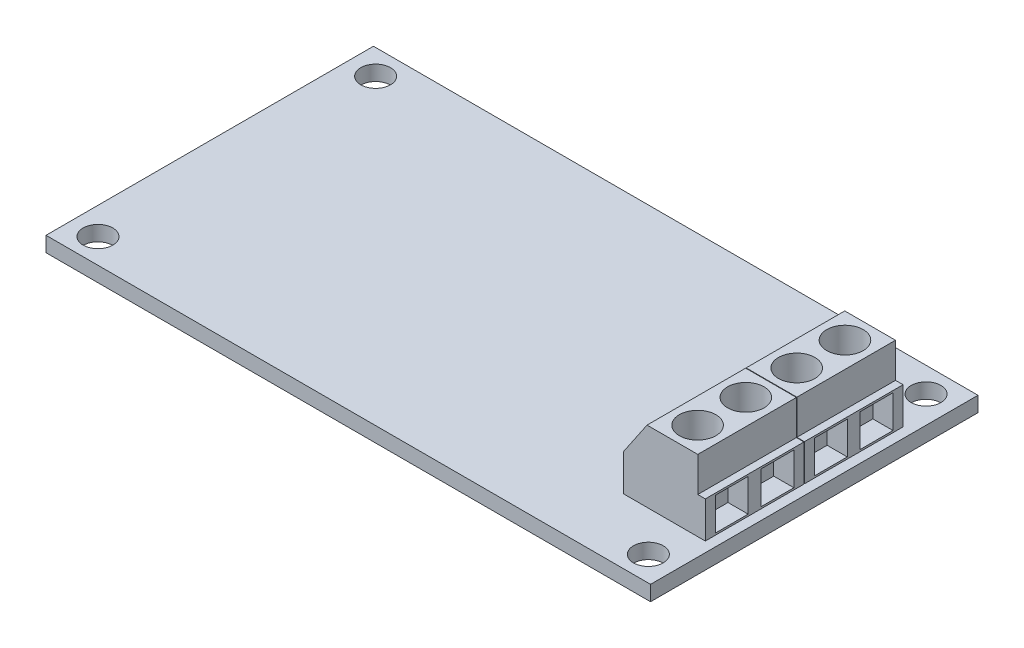
SolidWorks part; units mm, degrees
ref_plane "Plan de face" through (0, 0, 0) normal (0, 0, 1) x (1, 0, 0)
ref_plane "Plan de dessus" through (0, 0, 0) normal (0, 1, 0) x (1, 0, 0)
ref_plane "Plan de droite" through (0, 0, 0) normal (1, 0, 0) x (0, 0, -1)
sketch "Esquisse1" plane through (0, 0, 0) normal (0, 1, 0) x (1, 0, 0)
  line L1 (-30.48, 16.51) -> (30.48, 16.51)
  line L2 (-30.48, 16.51) -> (-30.48, -16.51)
  line L3 (-30.48, -16.51) -> (30.48, -16.51)
  line L4 (30.48, 16.51) -> (30.48, -16.51)
  line L5 (-30.48, 16.51) -> (30.48, -16.51) construction
  line L6 (-30.48, -16.51) -> (30.48, 16.51) construction
  point P0 (0, 0)
  dimension "D1" = 60.96
  dimension "D2" = 33.02
extrude "Boss.-Extru.1" add sketch "Esquisse1" along normal blind 1.524
sketch "Esquisse3" plane through (0, 1.524, 0) normal (0, 1, 0) x (1, 0, 0)
  line L0 (30.48, 0) -> (29.464, 0) construction
  line L1 (30.48, -16.51) -> (30.48, 16.51) construction
  line L2 (29.464, -9.9695) -> (29.464, 9.9695)
  line L3 (29.464, 9.9695) -> (21.209, 9.9695)
  line L4 (21.209, 9.9695) -> (21.209, -9.9695)
  line L5 (21.209, 0) -> (29.464, 0)
  line L6 (29.464, 0) -> (0, 0) construction
  line L7 (29.464, -9.9695) -> (21.209, -9.9695)
  dimension "D1" = 1.016
  dimension "D2" = 9.9695
  dimension "D3" = 8.255
extrude "Boss.-Extru.2" add sketch "Esquisse3" along normal blind 3.683 contours L7 L2 L5 L4 | L4 L5 L2 L3
sketch "Esquisse5" plane through (0, 5.207, 0) normal (0, 1, 0) x (1, 0, 0)
  line L0 (30.48, 0) -> (28.702, 0) construction
  line L1 (30.48, -16.51) -> (30.48, 16.51) construction
  line L2 (28.702, 0) -> (28.702, 9.9695)
  line L3 (29.464, 9.9695) -> (21.209, 9.9695) construction
  line L4 (28.702, 9.9695) -> (23.5862, 9.9695)
  line L5 (23.5862, 9.9695) -> (23.5862, -9.9695)
  line L6 (29.464, -9.9695) -> (21.209, -9.9695) construction
  line L7 (23.5862, -9.9695) -> (28.702, -9.9695)
  line L8 (28.702, -9.9695) -> (28.702, 0)
  dimension "D1" = 1.778
extrude "Boss.-Extru.3" add sketch "Esquisse5" along normal blind 3.5052
sketch "Esquisse6" plane through (0, 0, 9.9695) normal (0, 0, 1) x (1, 0, 0)
  line L0 (23.5862, 8.7122) -> (21.209, 5.207)
  line L1 (21.209, 5.207) -> (23.5862, 5.207)
  line L2 (23.5862, 5.207) -> (23.5862, 8.7122)
extrude "Boss.-Extru.4" add sketch "Esquisse6" against normal up to surface (19.939 mm away) up to face at (25.7403, 5.1626, -9.9695)
sketch "Esquisse7" plane through (0, 8.7122, 0) normal (0, 1, 0) x (1, 0, 0)
  line L0 (29.464, 0) -> (21.209, 0) construction
  line L1 (29.464, -9.9695) -> (29.464, 9.9695) construction
  line L2 (21.209, 9.9695) -> (21.209, -9.9695) construction
  line L4 (21.209, 0.0254) -> (29.464, 0.0254)
  line L5 (21.209, 0.0254) -> (21.209, -0.0254)
  line L6 (21.209, -0.0254) -> (29.464, -0.0254)
  line L7 (29.464, 0.0254) -> (29.464, -0.0254)
  line L8 (21.209, 0.0254) -> (29.464, -0.0254) construction
  line L9 (21.209, -0.0254) -> (29.464, 0.0254) construction
  point P6 (25.3365, 0)
  dimension "D1" = 0.0508
extrude "Enlèv. mat.-Extru.1" cut sketch "Esquisse7" against normal up to surface (7.1882 mm away)
sketch "Esquisse8" plane through (29.464, 0, 0) normal (1, 0, 0) x (0, 0, -1)
  line L0 (9.9695, 3.3655) -> (8.9535, 3.3655) construction
  line L1 (9.9695, 5.207) -> (9.9695, 1.524) construction
  line L3 (8.9535, 5.0165) -> (5.6515, 5.0165)
  line L4 (5.6515, 5.0165) -> (5.6515, 1.7145)
  line L5 (5.6515, 1.7145) -> (8.9535, 1.7145)
  line L7 (5.6515, 3.3655) -> (8.9535, 3.3655) construction
  line L8 (8.9535, 5.0165) -> (8.9535, 1.7145)
  line L9 (4.9974, 8.7122) -> (4.9974, 1.524) construction
  line L10 (0.0254, 8.7122) -> (9.9695, 8.7122) construction
  line L11 (0.0254, 1.524) -> (9.9695, 1.524) construction
  line L12 (4.3434, 1.7145) -> (1.0414, 1.7145)
  line L13 (1.0414, 5.0165) -> (1.0414, 1.7145)
  line L14 (1.0414, 5.0165) -> (4.3434, 5.0165)
  line L15 (4.3434, 5.0165) -> (4.3434, 1.7145)
  line L16 (0, 8.7122) -> (0, 1.524) construction
  line L17 (-8.9535, 5.0165) -> (-5.6515, 5.0165)
  line L18 (-5.6515, 5.0165) -> (-5.6515, 1.7145)
  line L19 (-5.6515, 1.7145) -> (-8.9535, 1.7145)
  line L20 (-8.9535, 5.0165) -> (-8.9535, 1.7145)
  line L21 (-4.3434, 5.0165) -> (-4.3434, 1.7145)
  line L22 (-1.0414, 5.0165) -> (-4.3434, 5.0165)
  line L23 (-1.0414, 5.0165) -> (-1.0414, 1.7145)
  line L24 (-4.3434, 1.7145) -> (-1.0414, 1.7145)
  dimension "D1" = 1.016
  dimension "D2" = 3.302
  dimension "D3" = 3.302
extrude "Enlèv. mat.-Extru.2" cut sketch "Esquisse8" against normal blind 2.032 contours L17 L18 L19 L20 | L21 L24 L23 L22 | L12 L13 L14 L15 | L8 L5 L4 L3
sketch "Esquisse9" plane through (0, 8.7122, 0) normal (0, 1, 0) x (1, 0, 0)
  line L0 (26.1441, 9.9695) -> (26.1441, 7.4295) construction
  line L1 (28.702, 9.9695) -> (23.5862, 9.9695) construction
  line L2 (23.5862, 4.9974) -> (28.702, 4.9974) construction
  line L3 (23.5862, 9.9695) -> (23.5862, 0.0254) construction
  line L4 (28.702, 0.0254) -> (28.702, 9.9695) construction
  line L5 (21.2097, 0) -> (31.7521, 0) construction
  circle A0 centre (26.1441, 7.4295) radius 1.8415
  circle A1 centre (26.1441, 2.5654) radius 1.8415
  circle A2 centre (26.1441, -2.5654) radius 1.8415
  circle A3 centre (26.1441, -7.4295) radius 1.8415
  dimension "D2" = 3.683
  dimension "D1" = 2.54
extrude "Enlèv. mat.-Extru.3" cut sketch "Esquisse9" against normal blind 3.683 contours A1 | A0 | A2 | A3
sketch "Esquisse10" plane through (0, 1.524, 0) normal (0, 1, 0) x (1, 0, 0)
  line L0 (27.73, 16.51) -> (27.73, 13.76) construction
  line L1 (30.48, 16.51) -> (-30.48, 16.51) construction
  line L2 (30.48, 13.76) -> (27.73, 13.76) construction
  line L3 (30.48, -16.51) -> (30.48, 16.51) construction
  line L4 (-30.48, 0) -> (44.9072, 0) construction
  line L5 (-30.48, 16.51) -> (-30.48, -16.51) construction
  line L6 (0, 16.51) -> (0, -23.0449) construction
  line L7 (-27.75, 0) -> (-27.75, 14) construction
  line L8 (0, 14) -> (-27.75, 14) construction
  circle A4 centre (-27.75, 14) radius 1.5
  circle A5 centre (27.75, 14) radius 1.5
  circle A6 centre (27.75, -14) radius 1.5
  circle A7 centre (-27.75, -14) radius 1.5
  dimension "D3" = 14
  dimension "D5" = 3
  dimension "D1" = 2.75
  dimension "D2" = 2.75
  dimension "D4" = 27.75
extrude "Enlèv. mat.-Extru.4" cut sketch "Esquisse10" against normal through all
